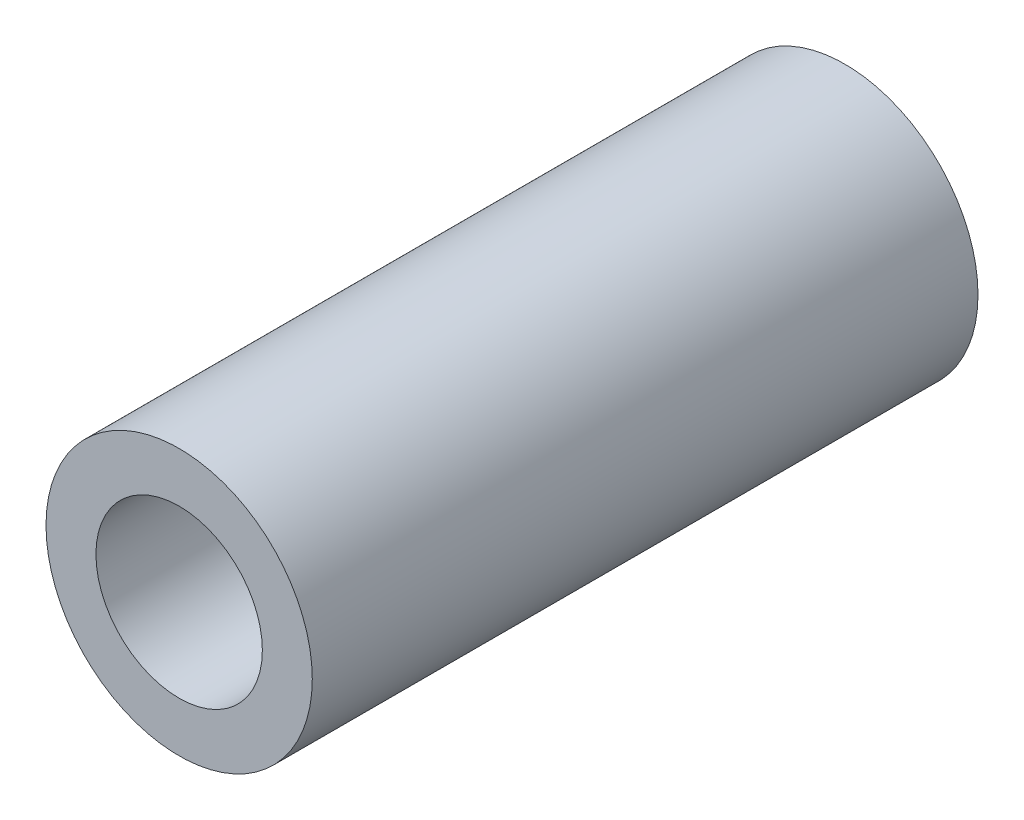
SolidWorks part; units mm, degrees
ref_plane "前视基准面" through (0, 0, 0) normal (0, 0, 1) x (1, 0, 0)
ref_plane "上视基准面" through (0, 0, 0) normal (0, 1, 0) x (1, 0, 0)
ref_plane "右视基准面" through (0, 0, 0) normal (1, 0, 0) x (0, 0, -1)
sketch "草图1" plane through (0, 0, 0) normal (0, 0, 1) x (1, 0, 0)
  circle A0 centre (0, 0) radius 2.5
  circle A1 centre (0, 0) radius 4
  dimension "D1" = 5
  dimension "D2" = 8
extrude "凸台-拉伸1" add sketch "草图1" along normal mid plane 20
